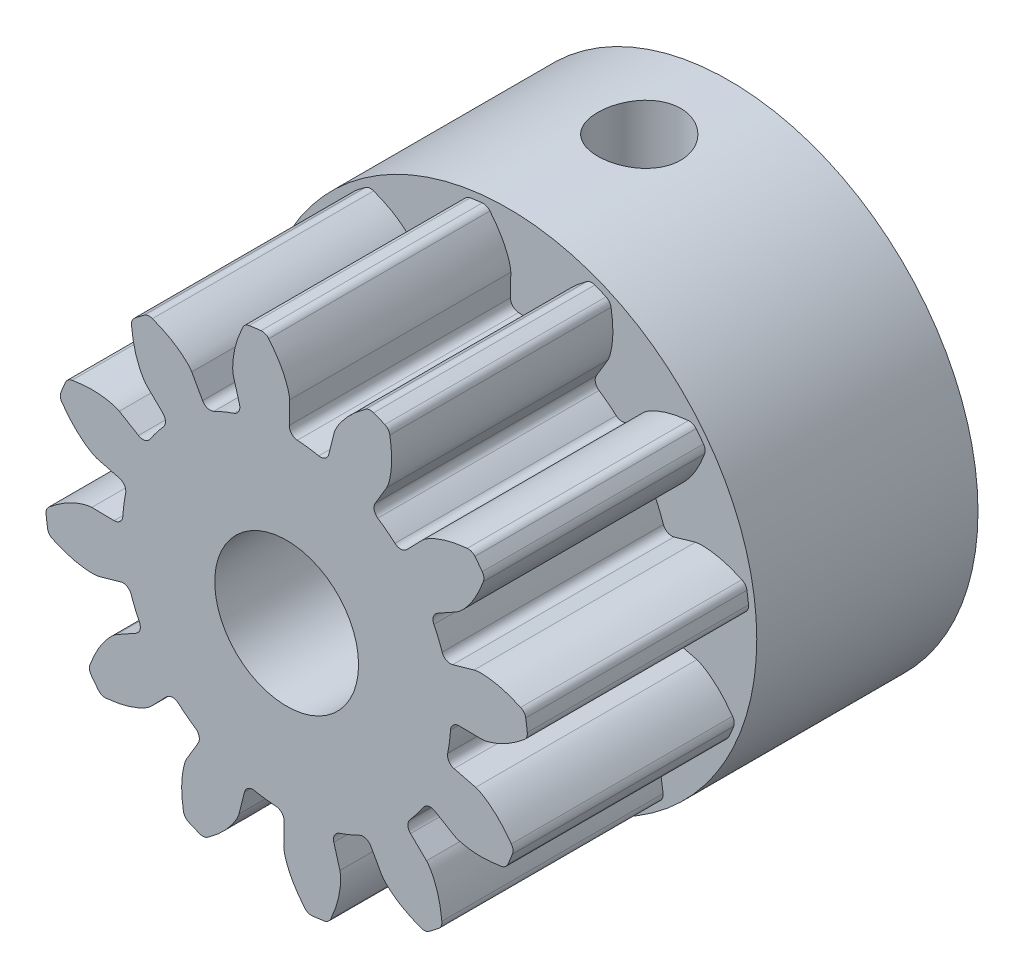
SolidWorks part; units mm, degrees
ref_plane "前视基准面" through (0, 0, 0) normal (0, 0, 1) x (1, 0, 0)
ref_plane "上视基准面" through (0, 0, 0) normal (0, 1, 0) x (1, 0, 0)
ref_plane "右视基准面" through (0, 0, 0) normal (1, 0, 0) x (0, 0, -1)
sketch "草图1" plane through (0, 0, 0) normal (0, 0, 1) x (1, 0, 0)
  line B0 (1.7219, 6.8341) -> (1.5251, 6.053)
  line B1 (3.6149, 6.05) -> (3.2017, 5.3585)
  line B2 (4.9083, 5.0575) -> (4.3473, 4.4795)
  line B3 (6.1556, 3.432) -> (5.452, 3.0398)
  line B4 (6.7795, 1.9258) -> (6.0046, 1.7057)
  line B5 (7.0469, -0.1055) -> (6.2415, -0.0935)
  line B6 (6.8341, -1.7219) -> (6.053, -1.5251)
  line B7 (6.05, -3.6149) -> (5.3585, -3.2017)
  line B8 (5.0575, -4.9083) -> (4.4795, -4.3473)
  line B9 (3.432, -6.1556) -> (3.0398, -5.452)
  line B10 (1.9258, -6.7795) -> (1.7057, -6.0046)
  line B11 (-0.1055, -7.0469) -> (-0.0935, -6.2415)
  line B12 (-1.7219, -6.8341) -> (-1.5251, -6.053)
  line B13 (-3.6149, -6.05) -> (-3.2017, -5.3585)
  line B14 (-4.9083, -5.0575) -> (-4.3473, -4.4795)
  line B15 (-6.1556, -3.432) -> (-5.452, -3.0398)
  line B16 (-6.7795, -1.9258) -> (-6.0046, -1.7057)
  line B17 (-7.0469, 0.1055) -> (-6.2415, 0.0935)
  line B18 (-6.8341, 1.7219) -> (-6.053, 1.5251)
  line B19 (-6.05, 3.6149) -> (-5.3585, 3.2017)
  line B20 (-5.0575, 4.9083) -> (-4.4795, 4.3473)
  line B21 (-3.432, 6.1556) -> (-3.0398, 5.452)
  line B22 (0.1055, 7.0469) -> (0.0935, 6.2415)
  line B23 (-1.9258, 6.7795) -> (-1.7057, 6.0046)
  arc B24 (3.5487, 7.9981) -> (3.1462, 8.1648) centre (0, 0) ccw
  arc B25 (1.161, 5.8229) -> (0.775, 5.8867) centre (0, 0) ccw
  arc B26 (3.2017, 5.3585) -> (3.2965, 4.9383) centre (3.47, 5.1983) ccw
  arc B27 (1.161, 5.8229) -> (1.5251, 6.053) centre (1.2221, 6.1294) ccw
  arc B28 (3.1462, 8.1648) -> (2.8493, 8.1254) centre (3.0339, 7.8732) ccw
  arc B29 (3.7307, 7.7603) -> (3.5487, 7.9981) centre (3.4219, 7.7125) ccw
  arc B30 (3.6145, 4.7105) -> (3.2965, 4.9383) centre (0, 0) ccw
  arc B31 (7.0723, 5.1522) -> (6.8071, 5.4978) centre (0, 0) ccw
  arc B32 (3.9169, 4.4623) -> (3.6145, 4.7105) centre (0, 0) ccw
  arc B33 (5.452, 3.0398) -> (5.324, 2.6285) centre (5.6042, 2.7668) ccw
  arc B34 (3.9169, 4.4623) -> (4.3473, 4.4795) centre (4.123, 4.6971) ccw
  arc B35 (6.8071, 5.4978) -> (6.5303, 5.6121) centre (6.564, 5.3014) ccw
  arc B36 (7.1111, 4.8553) -> (7.0723, 5.1522) centre (6.8197, 4.9682) ccw
  arc B37 (5.4855, 2.2722) -> (5.324, 2.6285) centre (0, 0) ccw
  arc B38 (8.7009, 0.9258) -> (8.644, 1.3577) centre (0, 0) ccw
  arc B39 (5.6233, 1.906) -> (5.4855, 2.2722) centre (0, 0) ccw
  arc B40 (6.2415, -0.0935) -> (5.925, -0.3856) centre (6.2368, -0.4059) ccw
  arc B41 (5.6233, 1.906) -> (6.0046, 1.7057) centre (5.9192, 2.0063) ccw
  arc B42 (8.644, 1.3577) -> (8.4615, 1.5951) centre (8.3353, 1.3092) ccw
  arc B43 (8.586, 0.6492) -> (8.7009, 0.9258) centre (8.3901, 0.8928) ccw
  arc B44 (5.8867, -0.775) -> (5.925, -0.3856) centre (0, 0) ccw
  arc B45 (7.9981, -3.5487) -> (8.1648, -3.1462) centre (0, 0) ccw
  arc B46 (5.8229, -1.161) -> (5.8867, -0.775) centre (0, 0) ccw
  arc B47 (5.3585, -3.2017) -> (4.9383, -3.2965) centre (5.1983, -3.47) ccw
  arc B48 (5.8229, -1.161) -> (6.053, -1.5251) centre (6.1294, -1.2221) ccw
  arc B49 (8.1648, -3.1462) -> (8.1254, -2.8493) centre (7.8732, -3.0339) ccw
  arc B50 (7.7603, -3.7307) -> (7.9981, -3.5487) centre (7.7125, -3.4219) ccw
  arc B51 (4.7105, -3.6145) -> (4.9383, -3.2965) centre (0, 0) ccw
  arc B52 (5.1522, -7.0723) -> (5.4978, -6.8071) centre (0, 0) ccw
  arc B53 (4.4623, -3.9169) -> (4.7105, -3.6145) centre (0, 0) ccw
  arc B54 (3.0398, -5.452) -> (2.6285, -5.324) centre (2.7668, -5.6042) ccw
  arc B55 (4.4623, -3.9169) -> (4.4795, -4.3473) centre (4.6971, -4.123) ccw
  arc B56 (5.4978, -6.8071) -> (5.6121, -6.5303) centre (5.3014, -6.564) ccw
  arc B57 (4.8553, -7.1111) -> (5.1522, -7.0723) centre (4.9682, -6.8197) ccw
  arc B58 (2.2722, -5.4855) -> (2.6285, -5.324) centre (0, 0) ccw
  arc B59 (0.9258, -8.7009) -> (1.3577, -8.644) centre (0, 0) ccw
  arc B60 (1.906, -5.6233) -> (2.2722, -5.4855) centre (0, 0) ccw
  arc B61 (-0.0935, -6.2415) -> (-0.3856, -5.925) centre (-0.4059, -6.2368) ccw
  arc B62 (1.906, -5.6233) -> (1.7057, -6.0046) centre (2.0063, -5.9192) ccw
  arc B63 (1.3577, -8.644) -> (1.5951, -8.4615) centre (1.3092, -8.3353) ccw
  arc B64 (0.6492, -8.586) -> (0.9258, -8.7009) centre (0.8928, -8.3901) ccw
  arc B65 (-0.775, -5.8867) -> (-0.3856, -5.925) centre (0, 0) ccw
  arc B66 (-3.5487, -7.9981) -> (-3.1462, -8.1648) centre (0, 0) ccw
  arc B67 (-1.161, -5.8229) -> (-0.775, -5.8867) centre (0, 0) ccw
  arc B68 (-3.2017, -5.3585) -> (-3.2965, -4.9383) centre (-3.47, -5.1983) ccw
  arc B69 (-1.161, -5.8229) -> (-1.5251, -6.053) centre (-1.2221, -6.1294) ccw
  arc B70 (-3.1462, -8.1648) -> (-2.8493, -8.1254) centre (-3.0339, -7.8732) ccw
  arc B71 (-3.7307, -7.7603) -> (-3.5487, -7.9981) centre (-3.4219, -7.7125) ccw
  arc B72 (-3.6145, -4.7105) -> (-3.2965, -4.9383) centre (0, 0) ccw
  arc B73 (-7.0723, -5.1522) -> (-6.8071, -5.4978) centre (0, 0) ccw
  arc B74 (-3.9169, -4.4623) -> (-3.6145, -4.7105) centre (0, 0) ccw
  arc B75 (-5.452, -3.0398) -> (-5.324, -2.6285) centre (-5.6042, -2.7668) ccw
  arc B76 (-3.9169, -4.4623) -> (-4.3473, -4.4795) centre (-4.123, -4.6971) ccw
  arc B77 (-6.8071, -5.4978) -> (-6.5303, -5.6121) centre (-6.564, -5.3014) ccw
  arc B78 (-7.1111, -4.8553) -> (-7.0723, -5.1522) centre (-6.8197, -4.9682) ccw
  arc B79 (-5.4855, -2.2722) -> (-5.324, -2.6285) centre (0, 0) ccw
  arc B80 (-8.7009, -0.9258) -> (-8.644, -1.3577) centre (0, 0) ccw
  arc B81 (-5.6233, -1.906) -> (-5.4855, -2.2722) centre (0, 0) ccw
  arc B82 (-6.2415, 0.0935) -> (-5.925, 0.3856) centre (-6.2368, 0.4059) ccw
  arc B83 (-5.6233, -1.906) -> (-6.0046, -1.7057) centre (-5.9192, -2.0063) ccw
  arc B84 (-8.644, -1.3577) -> (-8.4615, -1.5951) centre (-8.3353, -1.3092) ccw
  arc B85 (-8.586, -0.6492) -> (-8.7009, -0.9258) centre (-8.3901, -0.8928) ccw
  arc B86 (-5.8867, 0.775) -> (-5.925, 0.3856) centre (0, 0) ccw
  arc B87 (-7.9981, 3.5487) -> (-8.1648, 3.1462) centre (0, 0) ccw
  arc B88 (-5.8229, 1.161) -> (-5.8867, 0.775) centre (0, 0) ccw
  arc B89 (-5.3585, 3.2017) -> (-4.9383, 3.2965) centre (-5.1983, 3.47) ccw
  arc B90 (-5.8229, 1.161) -> (-6.053, 1.5251) centre (-6.1294, 1.2221) ccw
  arc B91 (-8.1648, 3.1462) -> (-8.1254, 2.8493) centre (-7.8732, 3.0339) ccw
  arc B92 (-7.7603, 3.7307) -> (-7.9981, 3.5487) centre (-7.7125, 3.4219) ccw
  arc B93 (-4.7105, 3.6145) -> (-4.9383, 3.2965) centre (0, 0) ccw
  arc B94 (-5.1522, 7.0723) -> (-5.4978, 6.8071) centre (0, 0) ccw
  arc B95 (-4.4623, 3.9169) -> (-4.7105, 3.6145) centre (0, 0) ccw
  arc B96 (-3.0398, 5.452) -> (-2.6285, 5.324) centre (-2.7668, 5.6042) ccw
  arc B97 (-4.4623, 3.9169) -> (-4.4795, 4.3473) centre (-4.6971, 4.123) ccw
  arc B98 (-5.4978, 6.8071) -> (-5.6121, 6.5303) centre (-5.3014, 6.564) ccw
  arc B99 (-4.8553, 7.1111) -> (-5.1522, 7.0723) centre (-4.9682, 6.8197) ccw
  arc B100 (-2.2722, 5.4855) -> (-2.6285, 5.324) centre (0, 0) ccw
  arc B101 (0.775, 5.8867) -> (0.3856, 5.925) centre (0, 0) ccw
  arc B102 (-0.6492, 8.586) -> (-0.9258, 8.7009) centre (-0.8928, 8.3901) ccw
  arc B103 (-1.3577, 8.644) -> (-1.5951, 8.4615) centre (-1.3092, 8.3353) ccw
  arc B104 (-1.906, 5.6233) -> (-1.7057, 6.0046) centre (-2.0063, 5.9192) ccw
  arc B105 (0.0935, 6.2415) -> (0.3856, 5.925) centre (0.4059, 6.2368) ccw
  arc B106 (-1.906, 5.6233) -> (-2.2722, 5.4855) centre (0, 0) ccw
  arc B107 (-0.9258, 8.7009) -> (-1.3577, 8.644) centre (0, 0) ccw
  spline B108 degree 3 poles (2.8493, 8.1254) (2.71, 8.0234) (2.431, 7.8112) (2.0978, 7.4655) (1.8743, 7.156) (1.7632, 6.9544) (1.7302, 6.8582) (1.7219, 6.8341) knots 0.168804 0.168804 0.168804 0.168804 0.686225 1.219957 1.601196 1.829944 1.906214 1.906214 1.906214 1.906214
  spline B109 degree 3 poles (3.7307, 7.7603) (3.7572, 7.5897) (3.8044, 7.2424) (3.7956, 6.7622) (3.7347, 6.3854) (3.6707, 6.1643) (3.626, 6.0729) (3.6149, 6.05) knots 0.168804 0.168804 0.168804 0.168804 0.686225 1.219957 1.601196 1.829944 1.906214 1.906214 1.906214 1.906214
  spline B110 degree 3 poles (6.5303, 5.6121) (6.3586, 5.5935) (6.0109, 5.5492) (5.5495, 5.4164) (5.2012, 5.2601) (5.0042, 5.1411) (4.9275, 5.0743) (4.9083, 5.0575) knots 0.168804 0.168804 0.168804 0.168804 0.686225 1.219957 1.601196 1.829944 1.906214 1.906214 1.906214 1.906214
  spline B111 degree 3 poles (7.1111, 4.8553) (7.0486, 4.6942) (6.9159, 4.3699) (6.6682, 3.9585) (6.4271, 3.6625) (6.2611, 3.503) (6.1767, 3.4462) (6.1556, 3.432) knots 0.168804 0.168804 0.168804 0.168804 0.686225 1.219957 1.601196 1.829944 1.906214 1.906214 1.906214 1.906214
  spline B112 degree 3 poles (8.4615, 1.5951) (8.3035, 1.6648) (7.9802, 1.8003) (7.5142, 1.916) (7.1344, 1.9548) (6.9043, 1.9502) (6.8044, 1.9307) (6.7795, 1.9258) knots 0.168804 0.168804 0.168804 0.168804 0.686225 1.219957 1.601196 1.829944 1.906214 1.906214 1.906214 1.906214
  spline B113 degree 3 poles (8.586, 0.6492) (8.4514, 0.541) (8.1743, 0.3265) (7.7541, 0.0941) (7.3973, -0.0417) (7.1738, -0.0968) (7.0723, -0.1038) (7.0469, -0.1055) knots 0.168804 0.168804 0.168804 0.168804 0.686225 1.219957 1.601196 1.829944 1.906214 1.906214 1.906214 1.906214
  spline B114 degree 3 poles (8.1254, -2.8493) (8.0234, -2.71) (7.8112, -2.431) (7.4655, -2.0978) (7.156, -1.8743) (6.9544, -1.7632) (6.8582, -1.7302) (6.8341, -1.7219) knots 0.168804 0.168804 0.168804 0.168804 0.686225 1.219957 1.601196 1.829944 1.906214 1.906214 1.906214 1.906214
  spline B115 degree 3 poles (7.7603, -3.7307) (7.5897, -3.7572) (7.2424, -3.8044) (6.7622, -3.7956) (6.3854, -3.7347) (6.1643, -3.6707) (6.0729, -3.626) (6.05, -3.6149) knots 0.168804 0.168804 0.168804 0.168804 0.686225 1.219957 1.601196 1.829944 1.906214 1.906214 1.906214 1.906214
  spline B116 degree 3 poles (5.6121, -6.5303) (5.5935, -6.3586) (5.5492, -6.0109) (5.4164, -5.5495) (5.2601, -5.2012) (5.1411, -5.0042) (5.0743, -4.9275) (5.0575, -4.9083) knots 0.168804 0.168804 0.168804 0.168804 0.686225 1.219957 1.601196 1.829944 1.906214 1.906214 1.906214 1.906214
  spline B117 degree 3 poles (4.8553, -7.1111) (4.6942, -7.0486) (4.3699, -6.9159) (3.9585, -6.6682) (3.6625, -6.4271) (3.503, -6.2611) (3.4462, -6.1767) (3.432, -6.1556) knots 0.168804 0.168804 0.168804 0.168804 0.686225 1.219957 1.601196 1.829944 1.906214 1.906214 1.906214 1.906214
  spline B118 degree 3 poles (1.5951, -8.4615) (1.6648, -8.3035) (1.8003, -7.9802) (1.916, -7.5142) (1.9548, -7.1344) (1.9502, -6.9043) (1.9307, -6.8044) (1.9258, -6.7795) knots 0.168804 0.168804 0.168804 0.168804 0.686225 1.219957 1.601196 1.829944 1.906214 1.906214 1.906214 1.906214
  spline B119 degree 3 poles (0.6492, -8.586) (0.541, -8.4514) (0.3265, -8.1743) (0.0941, -7.7541) (-0.0417, -7.3973) (-0.0968, -7.1738) (-0.1038, -7.0723) (-0.1055, -7.0469) knots 0.168804 0.168804 0.168804 0.168804 0.686225 1.219957 1.601196 1.829944 1.906214 1.906214 1.906214 1.906214
  spline B120 degree 3 poles (-2.8493, -8.1254) (-2.71, -8.0234) (-2.431, -7.8112) (-2.0978, -7.4655) (-1.8743, -7.156) (-1.7632, -6.9544) (-1.7302, -6.8582) (-1.7219, -6.8341) knots 0.168804 0.168804 0.168804 0.168804 0.686225 1.219957 1.601196 1.829944 1.906214 1.906214 1.906214 1.906214
  spline B121 degree 3 poles (-3.7307, -7.7603) (-3.7572, -7.5897) (-3.8044, -7.2424) (-3.7956, -6.7622) (-3.7347, -6.3854) (-3.6707, -6.1643) (-3.626, -6.0729) (-3.6149, -6.05) knots 0.168804 0.168804 0.168804 0.168804 0.686225 1.219957 1.601196 1.829944 1.906214 1.906214 1.906214 1.906214
  spline B122 degree 3 poles (-6.5303, -5.6121) (-6.3586, -5.5935) (-6.0109, -5.5492) (-5.5495, -5.4164) (-5.2012, -5.2601) (-5.0042, -5.1411) (-4.9275, -5.0743) (-4.9083, -5.0575) knots 0.168804 0.168804 0.168804 0.168804 0.686225 1.219957 1.601196 1.829944 1.906214 1.906214 1.906214 1.906214
  spline B123 degree 3 poles (-7.1111, -4.8553) (-7.0486, -4.6942) (-6.9159, -4.3699) (-6.6682, -3.9585) (-6.4271, -3.6625) (-6.2611, -3.503) (-6.1767, -3.4462) (-6.1556, -3.432) knots 0.168804 0.168804 0.168804 0.168804 0.686225 1.219957 1.601196 1.829944 1.906214 1.906214 1.906214 1.906214
  spline B124 degree 3 poles (-8.4615, -1.5951) (-8.3035, -1.6648) (-7.9802, -1.8003) (-7.5142, -1.916) (-7.1344, -1.9548) (-6.9043, -1.9502) (-6.8044, -1.9307) (-6.7795, -1.9258) knots 0.168804 0.168804 0.168804 0.168804 0.686225 1.219957 1.601196 1.829944 1.906214 1.906214 1.906214 1.906214
  spline B125 degree 3 poles (-8.586, -0.6492) (-8.4514, -0.541) (-8.1743, -0.3265) (-7.7541, -0.0941) (-7.3973, 0.0417) (-7.1738, 0.0968) (-7.0723, 0.1038) (-7.0469, 0.1055) knots 0.168804 0.168804 0.168804 0.168804 0.686225 1.219957 1.601196 1.829944 1.906214 1.906214 1.906214 1.906214
  spline B126 degree 3 poles (-8.1254, 2.8493) (-8.0234, 2.71) (-7.8112, 2.431) (-7.4655, 2.0978) (-7.156, 1.8743) (-6.9544, 1.7632) (-6.8582, 1.7302) (-6.8341, 1.7219) knots 0.168804 0.168804 0.168804 0.168804 0.686225 1.219957 1.601196 1.829944 1.906214 1.906214 1.906214 1.906214
  spline B127 degree 3 poles (-7.7603, 3.7307) (-7.5897, 3.7572) (-7.2424, 3.8044) (-6.7622, 3.7956) (-6.3854, 3.7347) (-6.1643, 3.6707) (-6.0729, 3.626) (-6.05, 3.6149) knots 0.168804 0.168804 0.168804 0.168804 0.686225 1.219957 1.601196 1.829944 1.906214 1.906214 1.906214 1.906214
  spline B128 degree 3 poles (-5.6121, 6.5303) (-5.5935, 6.3586) (-5.5492, 6.0109) (-5.4164, 5.5495) (-5.2601, 5.2012) (-5.1411, 5.0042) (-5.0743, 4.9275) (-5.0575, 4.9083) knots 0.168804 0.168804 0.168804 0.168804 0.686225 1.219957 1.601196 1.829944 1.906214 1.906214 1.906214 1.906214
  spline B129 degree 3 poles (-4.8553, 7.1111) (-4.6942, 7.0486) (-4.3699, 6.9159) (-3.9585, 6.6682) (-3.6625, 6.4271) (-3.503, 6.2611) (-3.4462, 6.1767) (-3.432, 6.1556) knots 0.168804 0.168804 0.168804 0.168804 0.686225 1.219957 1.601196 1.829944 1.906214 1.906214 1.906214 1.906214
  spline B130 degree 3 poles (-0.6492, 8.586) (-0.541, 8.4514) (-0.3265, 8.1743) (-0.0941, 7.7541) (0.0417, 7.3973) (0.0968, 7.1738) (0.1038, 7.0723) (0.1055, 7.0469) knots 0.168804 0.168804 0.168804 0.168804 0.686225 1.219957 1.601196 1.829944 1.906214 1.906214 1.906214 1.906214
  spline B131 degree 3 poles (-1.5951, 8.4615) (-1.6648, 8.3035) (-1.8003, 7.9802) (-1.916, 7.5142) (-1.9548, 7.1344) (-1.9502, 6.9043) (-1.9307, 6.8044) (-1.9258, 6.7795) knots 0.168804 0.168804 0.168804 0.168804 0.686225 1.219957 1.601196 1.829944 1.906214 1.906214 1.906214 1.906214
sketch_block_instance "块1-1"
sketch_block "块1"
extrude "凸台-拉伸1" add sketch "草图1" along normal blind 8
sketch "草图2" plane through (0, 0, 0) normal (0, 0, -1) x (-1, 0, 0)
  circle A0 centre (0, 0) radius 9
  dimension "D1" = 18
extrude "凸台-拉伸2" add sketch "草图2" along normal blind 8
sketch "草图3" plane through (0, 0, 8) normal (0, 0, 1) x (1, 0, 0)
  circle A0 centre (0, 0) radius 2.6
  dimension "D1" = 5.2
extrude "切除-拉伸1" cut sketch "草图3" against normal through all
sketch "草图4" plane through (0, 0, -8) normal (0, 0, -1) x (-1, 0, 0)
  line L1 (-2.8, 6.3) -> (2.8, 6.3)
  line L2 (-2.8, 6.3) -> (-2.8, 3.7)
  line L3 (-2.8, 3.7) -> (2.8, 3.7)
  line L4 (2.8, 6.3) -> (2.8, 3.7)
  dimension "D1" = 3.7
  dimension "D2" = 2.6
  dimension "D3" = 5.6
  dimension "D4" = 2.8
extrude "切除-拉伸2" cut sketch "草图4" against normal blind 6.5
sketch "草图5" plane through (0, 3.7, 0) normal (0, 1, 0) x (1, 0, 0)
  line L0 (9, 8) -> (-9, 8) construction
  circle A0 centre (0, 4.75) radius 1.5
  dimension "D1" = 3
  dimension "D2" = 3.25
extrude "切除-拉伸3" cut sketch "草图5" against normal up to next and the other way through all
